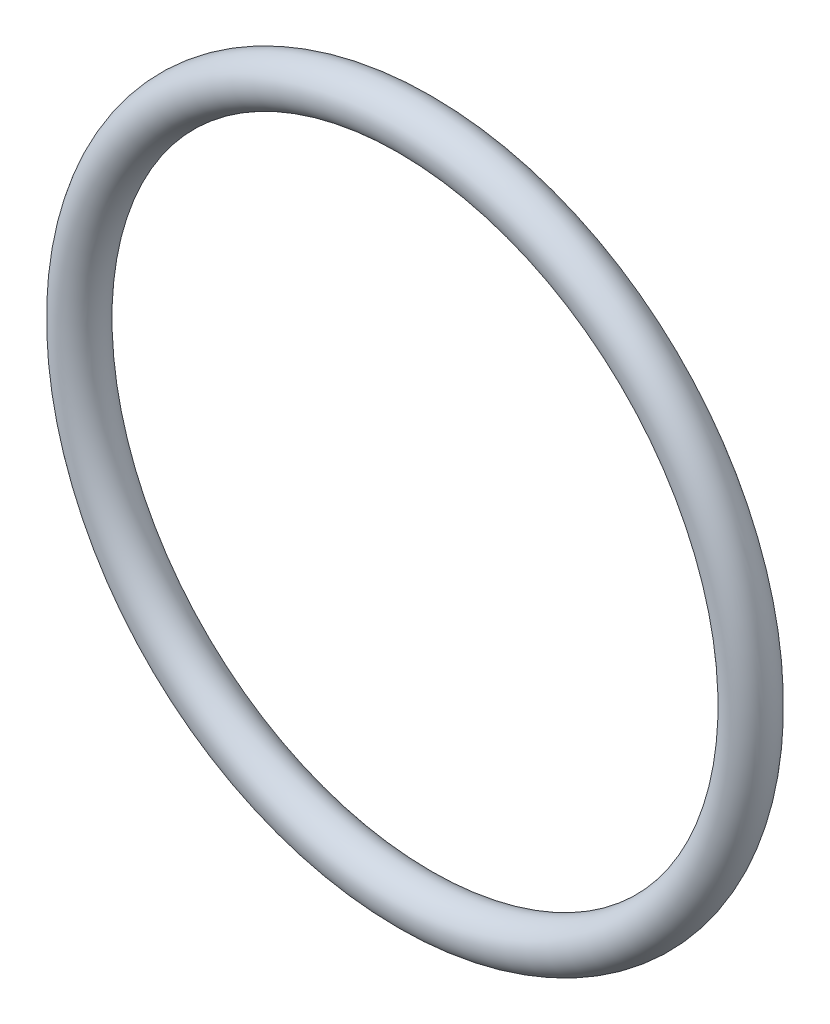
SolidWorks part; units mm, degrees
ref_plane "Plan de face" through (0, 0, 0) normal (0, 0, 1) x (1, 0, 0)
ref_plane "Plan de dessus" through (0, 0, 0) normal (0, 1, 0) x (1, 0, 0)
ref_plane "Plan de droite" through (0, 0, 0) normal (1, 0, 0) x (0, 0, -1)
sketch "Esquisse1" plane through (0, 0, 0) normal (0, 0, 1) x (1, 0, 0)
  circle A0 centre (0, 0) radius 28
sketch "Esquisse17" plane through (0, 0, 0) normal (1, 0, 0) x (0, 0, -1)
  line L0 (0, 0) -> (0, 29) construction
  line L1 (0, 28) -> (0, -28) construction
  circle A0 centre (0, 29) radius 2
ref_plane "Plan2" through (0, 0, 0) normal (1, 0, 0) x (0, 0, -1)
sweep "Balayage2" add profiles "Esquisse17" path "Esquisse1"
sketch "Esquisse18" plane through (0, 0, 0) normal (0, 0, 1) x (1, 0, 0)
  circle A0 centre (0, 0) radius 28
